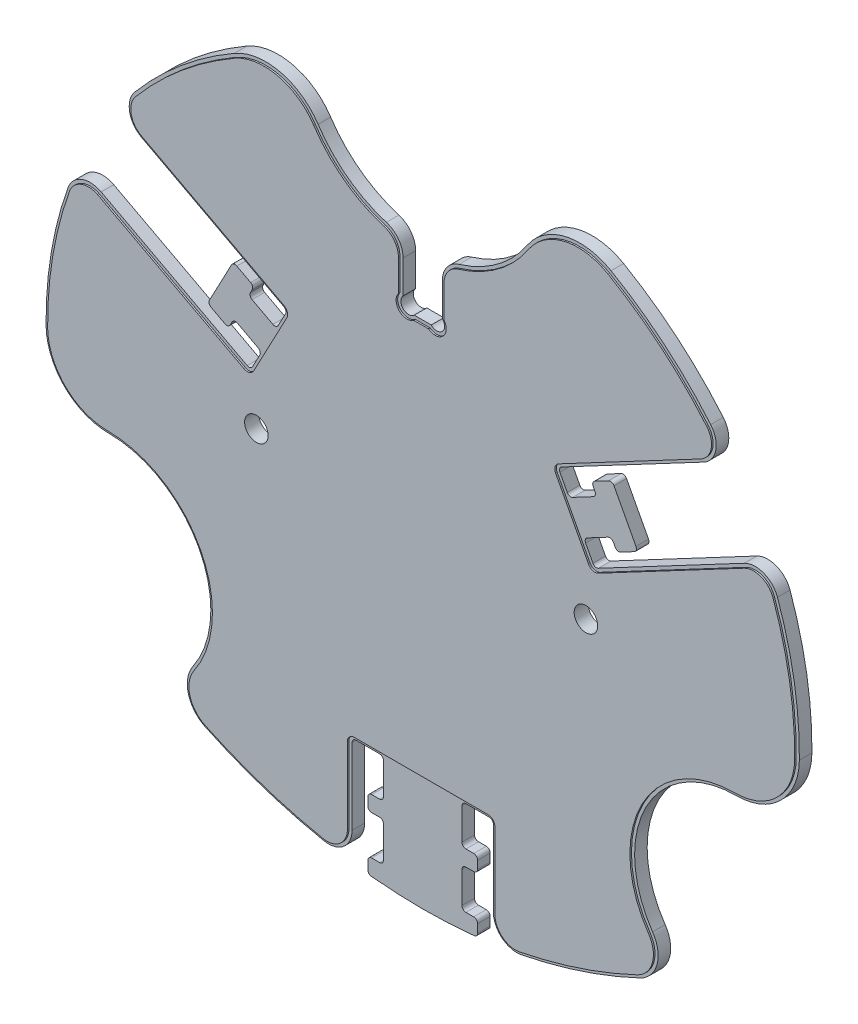
SolidWorks part; units mm, degrees
ref_plane "Plan de face" through (0, 0, 0) normal (0, 0, 1) x (1, 0, 0)
ref_plane "Plan de dessus" through (0, 0, 0) normal (0, 1, 0) x (1, 0, 0)
ref_plane "Plan de droite" through (0, 0, 0) normal (1, 0, 0) x (0, 0, -1)
sketch "Esquisse1" plane through (0, 0, 0) normal (0, 0, 1) x (1, 0, 0)
  line L0 (-25, 70) -> (-25, 0) construction
  line L1 (-25, 0) -> (25, 0) construction
  line L2 (25, 0) -> (25, 70) construction
  line L3 (25, 70) -> (-25, 70) construction
  line L4 (0, 70) -> (0, 0) construction
  line L5 (-25, 42.594) -> (25, 42.594) construction
  line L6 (15.5429, -26.8302) -> (15.4017, -26.5477) construction
  line L7 (40, 19.5) -> (0, 42.594) construction
  line L8 (0, 42.594) -> (-40, 19.5) construction
  line L9 (41.6817, 64.6801) -> (0, 42.594) construction
  line L10 (0, 0) -> (24.9579, 0) construction
  line L11 (43.9325, 60.2142) -> (21.9323, 48.5568)
  line L12 (21.9323, 48.5568) -> (20.5277, 51.2077)
  line L13 (20.5277, 51.2077) -> (24.0621, 53.0805)
  line L14 (24.0621, 53.0805) -> (24.7645, 51.7551)
  line L15 (24.7645, 51.7551) -> (27.4153, 53.1597)
  line L16 (27.4153, 53.1597) -> (24.1379, 59.345)
  line L17 (24.1379, 59.345) -> (21.487, 57.9404)
  line L18 (21.487, 57.9404) -> (22.1893, 56.615)
  line L19 (22.1893, 56.615) -> (18.6548, 54.7421)
  line L20 (18.6548, 54.7421) -> (17.2502, 57.393)
  line L21 (17.2502, 57.393) -> (38.9688, 68.9011)
  line L22 (-43.9325, 60.2142) -> (-21.9323, 48.5568)
  line L23 (-21.9323, 48.5568) -> (-20.5277, 51.2077)
  line L24 (-20.5277, 51.2077) -> (-24.0621, 53.0805)
  line L25 (-24.0621, 53.0805) -> (-24.7645, 51.7551)
  line L26 (-24.7645, 51.7551) -> (-27.4153, 53.1597)
  line L27 (-27.4153, 53.1597) -> (-24.1379, 59.345)
  line L28 (-24.1379, 59.345) -> (-21.487, 57.9404)
  line L29 (-21.487, 57.9404) -> (-22.1893, 56.615)
  line L30 (-22.1893, 56.615) -> (-18.6548, 54.7421)
  line L31 (-18.6548, 54.7421) -> (-17.2502, 57.393)
  line L32 (-17.2502, 57.393) -> (-38.9688, 68.9011)
  line L33 (-9, 0.6296) -> (-9, 14.3801)
  line L34 (-9, 14.3801) -> (-5, 14.3801)
  line L35 (-5, 14.3801) -> (-5, 2.3801) construction
  line L36 (-5, 2.3801) -> (-7, 2.3801)
  line L37 (-7, 2.3801) -> (-7, 0.3801)
  line L38 (-7, 0.3801) -> (7, 0.3801) construction
  line L39 (7, 0.3801) -> (7, 2.3801)
  line L40 (7, 2.3801) -> (5, 2.3801)
  line L41 (5, 2.3801) -> (5, 14.3801) construction
  line L42 (5, 14.3801) -> (9, 14.3801)
  line L43 (9, 14.3801) -> (9, 0.6296)
  line L44 (-5, 14.3801) -> (-5, 9.3801)
  line L45 (-5, 9.3801) -> (-7, 9.3801)
  line L46 (-7, 9.3801) -> (-7, 7.3801)
  line L47 (-7, 7.3801) -> (-5, 7.3801)
  line L48 (-5, 7.3801) -> (-5, 2.3801)
  line L49 (5, 7.3801) -> (5, 2.3801)
  line L50 (7, 7.3801) -> (5, 7.3801)
  line L51 (7, 9.3801) -> (7, 7.3801)
  line L52 (5, 9.3801) -> (7, 9.3801)
  line L53 (5, 14.3801) -> (5, 9.3801)
  line L54 (-2.5, 72.9786) -> (-2.5, 65) construction
  line L55 (-2.5, 65) -> (2.5, 65) construction
  line L56 (2.5, 65) -> (2.5, 72.9786) construction
  line L57 (2.5, 72.9786) -> (2.5, 66.4142)
  line L58 (1.0858, 65) -> (-1.0858, 65)
  line L59 (-2.5, 72.9786) -> (-2.5, 66.4142)
  line L60 (2.5, 65) -> (1.7929, 65.7071) construction
  circle A0 centre (40, 19.5) radius 10 construction
  circle A1 centre (-40, 19.5) radius 10 construction
  circle A2 centre (0, 88.782) radius 10 construction
  arc A3 (40, 32.5) -> (29.2941, 12.1254) centre (40, 19.5) ccw
  arc A4 (40, 32.5) -> (47.9997, 40.4255) centre (40, 40.5) ccw
  arc A5 (23.9998, 82.4438) -> (47.9997, 40.4255) centre (0, 40.8725) cw construction
  arc A6 (23.9998, 82.4438) -> (13.3333, 79.9377) centre (20, 75.5155) ccw
  arc A7 (13.3333, 79.9377) -> (-13.3333, 79.9377) centre (0, 88.782) cw construction
  arc A8 (29.2941, 12.1254) -> (27.7149, 6.2426) centre (26, 9.8563) cw
  arc A9 (27.7149, 6.2426) -> (-27.7149, 6.2426) centre (0, 64.6433) cw construction
  arc A10 (-29.2941, 12.1254) -> (-27.7149, 6.2426) centre (-26, 9.8563) ccw
  arc A11 (-40, 32.5) -> (-29.2941, 12.1254) centre (-40, 19.5) cw
  arc A12 (-40, 32.5) -> (-47.9997, 40.4255) centre (-40, 40.5) cw
  arc A13 (-23.9998, 82.4438) -> (-47.9997, 40.4255) centre (0, 40.8725) ccw construction
  arc A14 (-23.9998, 82.4438) -> (-13.3333, 79.9377) centre (-20, 75.5155) cw
  circle A15 centre (-21, 42.594) radius 1.5
  circle A16 centre (21, 42.594) radius 1.5
  arc A17 (23.9998, 82.4438) -> (38.9688, 68.9011) centre (0, 40.8725) cw
  arc A18 (43.9325, 60.2142) -> (47.9997, 40.4255) centre (0, 40.8725) cw
  arc A19 (-43.9325, 60.2142) -> (-47.9997, 40.4255) centre (0, 40.8725) ccw
  arc A20 (-23.9998, 82.4438) -> (-38.9688, 68.9011) centre (0, 40.8725) ccw
  arc A21 (9, 0.6296) -> (27.7149, 6.2426) centre (0, 64.6433) ccw
  arc A22 (-9, 0.6296) -> (-27.7149, 6.2426) centre (0, 64.6433) cw
  arc A23 (-7, 0.3801) -> (7, 0.3801) centre (0, 64.6433) ccw
  arc A24 (-2.5, 72.9786) -> (-13.3333, 79.9377) centre (0, 88.782) cw
  arc A25 (2.5, 72.9786) -> (13.3333, 79.9377) centre (0, 88.782) ccw
  arc A26 (2.5, 66.4142) -> (1.0858, 65) centre (1.7929, 65.7071) cw
  arc A27 (-2.5, 66.4142) -> (-1.0858, 65) centre (-1.7929, 65.7071) ccw
  point P10 (-21, 42.594)
  point P12 (21, 42.594)
  point P95 (9, 14.3801)
  point P96 (-9, 14.3801)
  point P111 (-1.1363, 65)
  dimension "D3" = 20
  dimension "D10" = 8
  dimension "D12" = 8
  dimension "D14" = 4
  dimension "D19" = 3
  dimension "D44" = 1
  dimension "D1" = 70
  dimension "D2" = 50
  dimension "D4" = 19.5
  dimension "D5" = 80
  dimension "D6" = 80
  dimension "D7" = 42
  dimension "D9" = 6
  dimension "D11" = 3
  dimension "D15" = 40
  dimension "D16" = 20
  dimension "D17" = 1
  dimension "D18" = 26
  dimension "D20" = 120
  dimension "D8" = 4
  dimension "D21" = 4
  dimension "D22" = 7
  dimension "D23" = 5
  dimension "D24" = 5
  dimension "D25" = 4
  dimension "D26" = 7
  dimension "D27" = 4
  dimension "D28" = 3
  dimension "D29" = 25
  dimension "D30" = 10
  dimension "D31" = 14
  dimension "D32" = 10
  dimension "D33" = 10
  dimension "D34" = 2
  dimension "D35" = 4
  dimension "D36" = 18
  dimension "D37" = 2
  dimension "D38" = 5
  dimension "D39" = 5
  dimension "D40" = 2
  dimension "D41" = 65
  dimension "D13" = 5
  dimension "D42" = 5
  dimension "D43" = 45
extrude "Boss.-Extru.1" add sketch "Esquisse1" along normal blind 1.6
fillet "Congé5" radius 0.5 38 edges at (-24.0621, 53.0805, 0.8) (-21.9323, 48.5568, 0.8) (-27.4153, 53.1597, 0.8) (-24.7645, 51.7551, 0.8) (-20.5277, 51.2077, 0.8) (-17.2502, 57.393, 0.8) (-18.6548, 54.7421, 0.8) (-22.1893, 56.615, 0.8) (-24.1379, 59.345, 0.8) (-21.487, 57.9404, 0.8) (17.2502, 57.393, 0.8) (18.6548, 54.7421, 0.8) (24.1379, 59.345, 0.8) (21.487, 57.9404, 0.8) (22.1893, 56.615, 0.8) (21.9323, 48.5568, 0.8) (20.5277, 51.2077, 0.8) (24.0621, 53.0805, 0.8) (24.7645, 51.7551, 0.8) (27.4153, 53.1597, 0.8) (9, 14.3801, 0.8) (-5, 14.3801, 0.8) (-7, 0.3801, 0.8) (7, 0.3801, 0.8) (5, 2.3801, 0.8) (7, 2.3801, 0.8) (-7, 2.3801, 0.8) (-5, 2.3801, 0.8) (-5, 9.3801, 0.8) (-7, 9.3801, 0.8) (-5, 7.3801, 0.8) (-7, 7.3801, 0.8) (-9, 14.3801, 0.8) (5, 7.3801, 0.8) (7, 7.3801, 0.8) (7, 9.3801, 0.8) (5, 9.3801, 0.8) (5, 14.3801, 0.8)
fillet "Congé6" radius 3 8 edges at (-38.9688, 68.9011, 0.8) (-43.9325, 60.2142, 0.8) (43.9325, 60.2142, 0.8) (38.9688, 68.9011, 0.8) (-9, 0.6296, 0.8) (9, 0.6296, 0.8) (2.5, 72.9786, 0.8) (-2.5, 72.9786, 0.8)
sketch "Esquisse2" plane through (0, 0, 1.6) normal (0, 0, 1) x (1, 0, 0)
  line L0 (17.1309, 56.7639) -> (21.3447, 48.8113)
  line L1 (8.5, 14.7801) -> (-8.5, 14.7801)
  line L2 (-17.1309, 56.7639) -> (-21.3447, 48.8113)
  line L22 (41.1662, 58.2957) -> (22.5614, 48.4375)
  line L23 (41.1662, 58.2957) -> (22.5614, 48.4375)
  line L24 (21.3447, 48.8113) -> (20.4083, 50.5786)
  line L25 (21.3447, 48.8113) -> (20.4083, 50.5786) construction
  line L26 (20.7822, 51.7952) -> (23.4331, 53.1998)
  line L27 (20.7822, 51.7952) -> (23.4331, 53.1998) construction
  line L28 (24.6497, 52.826) -> (24.8838, 52.3842)
  line L29 (24.6497, 52.826) -> (24.8838, 52.3842) construction
  line L30 (25.019, 52.3426) -> (26.7862, 53.279)
  line L31 (25.019, 52.3426) -> (26.7862, 53.279) construction
  line L32 (26.8278, 53.4142) -> (24.0185, 58.7159)
  line L33 (26.8278, 53.4142) -> (24.0185, 58.7159) construction
  line L34 (23.8833, 58.7575) -> (22.1161, 57.8211)
  line L35 (23.8833, 58.7575) -> (22.1161, 57.8211) construction
  line L36 (22.0746, 57.6859) -> (22.3087, 57.2441)
  line L37 (22.0746, 57.6859) -> (22.3087, 57.2441) construction
  line L38 (21.9348, 56.0274) -> (19.2839, 54.6228)
  line L39 (21.9348, 56.0274) -> (19.2839, 54.6228) construction
  line L40 (18.0673, 54.9967) -> (17.1309, 56.7639)
  line L41 (18.0673, 54.9967) -> (17.1309, 56.7639) construction
  line L42 (17.5047, 57.9806) -> (35.6237, 67.5813)
  line L43 (17.5047, 57.9806) -> (35.6237, 67.5813)
  line L44 (-35.6237, 67.5813) -> (-17.5047, 57.9806)
  line L45 (-35.6237, 67.5813) -> (-17.5047, 57.9806)
  line L46 (-17.1309, 56.7639) -> (-18.0673, 54.9967)
  line L47 (-17.1309, 56.7639) -> (-18.0673, 54.9967) construction
  line L48 (-19.2839, 54.6228) -> (-21.9348, 56.0274)
  line L49 (-19.2839, 54.6228) -> (-21.9348, 56.0274) construction
  line L50 (-22.3087, 57.2441) -> (-22.0746, 57.6859)
  line L51 (-22.3087, 57.2441) -> (-22.0746, 57.6859) construction
  line L52 (-22.1161, 57.8211) -> (-23.8833, 58.7575)
  line L53 (-22.1161, 57.8211) -> (-23.8833, 58.7575) construction
  line L54 (-24.0185, 58.7159) -> (-26.8278, 53.4142)
  line L55 (-24.0185, 58.7159) -> (-26.8278, 53.4142) construction
  line L56 (-26.7862, 53.279) -> (-25.019, 52.3426)
  line L57 (-26.7862, 53.279) -> (-25.019, 52.3426) construction
  line L58 (-24.8838, 52.3842) -> (-24.6497, 52.826)
  line L59 (-24.8838, 52.3842) -> (-24.6497, 52.826) construction
  line L60 (-23.4331, 53.1998) -> (-20.7822, 51.7952)
  line L61 (-23.4331, 53.1998) -> (-20.7822, 51.7952) construction
  line L62 (-20.4083, 50.5786) -> (-21.3447, 48.8113)
  line L63 (-20.4083, 50.5786) -> (-21.3447, 48.8113) construction
  line L64 (-22.5614, 48.4375) -> (-41.1662, 58.2957)
  line L65 (-22.5614, 48.4375) -> (-41.1662, 58.2957)
  line L87 (-9.4, 4.1793) -> (-9.4, 13.8801)
  line L88 (-9.4, 4.1793) -> (-9.4, 13.8801)
  line L89 (-8.5, 14.7801) -> (-5.5, 14.7801)
  line L90 (-8.5, 14.7801) -> (-5.5, 14.7801) construction
  line L91 (-4.6, 13.8801) -> (-4.6, 9.8801)
  line L92 (-4.6, 13.8801) -> (-4.6, 9.8801) construction
  line L93 (-5.5, 8.9801) -> (-6.5, 8.9801)
  line L94 (-5.5, 8.9801) -> (-6.5, 8.9801) construction
  line L95 (-6.6, 8.8801) -> (-6.6, 7.8801)
  line L96 (-6.6, 8.8801) -> (-6.6, 7.8801) construction
  line L97 (-6.5, 7.7801) -> (-5.5, 7.7801)
  line L98 (-6.5, 7.7801) -> (-5.5, 7.7801) construction
  line L99 (-4.6, 6.8801) -> (-4.6, 2.8801)
  line L100 (-4.6, 6.8801) -> (-4.6, 2.8801) construction
  line L101 (-5.5, 1.9801) -> (-6.5, 1.9801)
  line L102 (-5.5, 1.9801) -> (-6.5, 1.9801) construction
  line L103 (-6.6, 1.8801) -> (-6.6, 0.8302)
  line L104 (-6.6, 1.8801) -> (-6.6, 0.8302) construction
  line L105 (6.6, 0.8302) -> (6.6, 1.8801)
  line L106 (6.6, 0.8302) -> (6.6, 1.8801) construction
  line L107 (6.5, 1.9801) -> (5.5, 1.9801)
  line L108 (6.5, 1.9801) -> (5.5, 1.9801) construction
  line L109 (4.6, 2.8801) -> (4.6, 6.8801)
  line L110 (4.6, 2.8801) -> (4.6, 6.8801) construction
  line L111 (5.5, 7.7801) -> (6.5, 7.7801)
  line L112 (5.5, 7.7801) -> (6.5, 7.7801) construction
  line L113 (6.6, 7.8801) -> (6.6, 8.8801)
  line L114 (6.6, 7.8801) -> (6.6, 8.8801) construction
  line L115 (6.5, 8.9801) -> (5.5, 8.9801)
  line L116 (6.5, 8.9801) -> (5.5, 8.9801) construction
  line L117 (4.6, 9.8801) -> (4.6, 13.8801)
  line L118 (4.6, 9.8801) -> (4.6, 13.8801) construction
  line L119 (5.5, 14.7801) -> (8.5, 14.7801)
  line L120 (5.5, 14.7801) -> (8.5, 14.7801) construction
  line L121 (9.4, 13.8801) -> (9.4, 4.1793)
  line L122 (9.4, 13.8801) -> (9.4, 4.1793)
  line L123 (2.9, 70.5955) -> (2.9, 66.564)
  line L124 (2.9, 70.5955) -> (2.9, 66.564)
  line L125 (0.936, 64.6) -> (-0.936, 64.6)
  line L126 (0.936, 64.6) -> (-0.936, 64.6)
  line L127 (-2.9, 66.564) -> (-2.9, 70.5955)
  line L128 (-2.9, 66.564) -> (-2.9, 70.5955)
  circle A19 centre (-21, 42.594) radius 1.5
  circle A20 centre (21, 42.594) radius 1.5
  circle A21 centre (21, 42.594) radius 1.5 construction
  circle A22 centre (-21, 42.594) radius 1.5 construction
  arc A25 (-44.8323, 56.8722) -> (-47.5997, 40.4292) centre (0, 40.8725) ccw
  arc A26 (23.7998, 82.0974) -> (13.6667, 79.7166) centre (20, 75.5155) ccw
  arc A27 (-36.3942, 71.5546) -> (-35.6237, 67.5813) centre (-34.4063, 69.8787) ccw
  arc A28 (-13.6667, 79.7166) -> (-23.7998, 82.0974) centre (-20, 75.5155) ccw
  arc A29 (-44.8323, 56.8722) -> (-47.5997, 40.4292) centre (0, 40.8725) ccw
  arc A30 (-47.5997, 40.4292) -> (-40, 32.9) centre (-40, 40.5) ccw
  arc A31 (-28.9647, 11.8985) -> (-40, 32.9) centre (-40, 19.5) ccw
  arc A32 (-28.9647, 11.8985) -> (-27.5435, 6.604) centre (-26, 9.8563) ccw
  arc A33 (-36.3942, 71.5546) -> (-35.6237, 67.5813) centre (-34.4063, 69.8787) ccw
  arc A34 (27.5435, 6.604) -> (28.9647, 11.8985) centre (26, 9.8563) ccw
  arc A35 (40, 32.9) -> (28.9647, 11.8985) centre (40, 19.5) ccw
  arc A36 (40, 32.9) -> (47.5997, 40.4292) centre (40, 40.5) ccw
  arc A38 (23.7998, 82.0974) -> (13.6667, 79.7166) centre (20, 75.5155) ccw
  arc A40 (-13.6667, 79.7166) -> (-23.7998, 82.0974) centre (-20, 75.5155) ccw
  arc A42 (-47.5997, 40.4292) -> (-40, 32.9) centre (-40, 40.5) ccw
  arc A43 (-28.9647, 11.8985) -> (-40, 32.9) centre (-40, 19.5) ccw
  arc A44 (-28.9647, 11.8985) -> (-27.5435, 6.604) centre (-26, 9.8563) ccw
  arc A46 (27.5435, 6.604) -> (28.9647, 11.8985) centre (26, 9.8563) ccw
  arc A47 (40, 32.9) -> (28.9647, 11.8985) centre (40, 19.5) ccw
  arc A48 (40, 32.9) -> (47.5997, 40.4292) centre (40, 40.5) ccw
  arc A61 (47.5997, 40.4292) -> (44.8323, 56.8722) centre (0, 40.8725) ccw
  arc A62 (47.5997, 40.4292) -> (44.8323, 56.8722) centre (0, 40.8725) ccw
  arc A63 (36.3942, 71.5546) -> (23.7998, 82.0974) centre (0, 40.8725) ccw
  arc A64 (36.3942, 71.5546) -> (23.7998, 82.0974) centre (0, 40.8725) ccw
  arc A65 (-23.7998, 82.0974) -> (-36.3942, 71.5546) centre (0, 40.8725) ccw
  arc A66 (-23.7998, 82.0974) -> (-36.3942, 71.5546) centre (0, 40.8725) ccw
  arc A96 (-17.1309, 56.7639) -> (-17.5047, 57.9806) centre (-17.9261, 57.1853) ccw
  arc A97 (-17.1309, 56.7639) -> (-17.5047, 57.9806) centre (-17.9261, 57.1853) ccw
  arc A98 (-19.2839, 54.6228) -> (-18.0673, 54.9967) centre (-18.8625, 55.4181) ccw
  arc A99 (-19.2839, 54.6228) -> (-18.0673, 54.9967) centre (-18.8625, 55.4181) ccw construction
  arc A100 (-22.3087, 57.2441) -> (-21.9348, 56.0274) centre (-21.5134, 56.8227) ccw
  arc A101 (-22.3087, 57.2441) -> (-21.9348, 56.0274) centre (-21.5134, 56.8227) ccw construction
  arc A102 (-22.0746, 57.6859) -> (-22.1161, 57.8211) centre (-22.1629, 57.7327) ccw
  arc A103 (-22.0746, 57.6859) -> (-22.1161, 57.8211) centre (-22.1629, 57.7327) ccw construction
  arc A104 (-23.8833, 58.7575) -> (-24.0185, 58.7159) centre (-23.9302, 58.6691) ccw
  arc A105 (-23.8833, 58.7575) -> (-24.0185, 58.7159) centre (-23.9302, 58.6691) ccw construction
  arc A106 (-26.8278, 53.4142) -> (-26.7862, 53.279) centre (-26.7394, 53.3674) ccw
  arc A107 (-26.8278, 53.4142) -> (-26.7862, 53.279) centre (-26.7394, 53.3674) ccw construction
  arc A108 (-25.019, 52.3426) -> (-24.8838, 52.3842) centre (-24.9722, 52.431) ccw
  arc A109 (-25.019, 52.3426) -> (-24.8838, 52.3842) centre (-24.9722, 52.431) ccw construction
  arc A110 (-23.4331, 53.1998) -> (-24.6497, 52.826) centre (-23.8544, 52.4046) ccw
  arc A111 (-23.4331, 53.1998) -> (-24.6497, 52.826) centre (-23.8544, 52.4046) ccw construction
  arc A112 (-20.4083, 50.5786) -> (-20.7822, 51.7952) centre (-21.2036, 51) ccw
  arc A113 (-20.4083, 50.5786) -> (-20.7822, 51.7952) centre (-21.2036, 51) ccw construction
  arc A114 (-22.5614, 48.4375) -> (-21.3447, 48.8113) centre (-22.14, 49.2327) ccw
  arc A115 (-22.5614, 48.4375) -> (-21.3447, 48.8113) centre (-22.14, 49.2327) ccw
  arc A116 (-41.1662, 58.2957) -> (-44.8323, 56.8722) centre (-42.3836, 55.9983) ccw
  arc A117 (-41.1662, 58.2957) -> (-44.8323, 56.8722) centre (-42.3836, 55.9983) ccw
  arc A118 (-27.5435, 6.604) -> (-12.5061, 1.629) centre (0, 64.6433) ccw
  arc A119 (-27.5435, 6.604) -> (-12.5061, 1.629) centre (0, 64.6433) ccw
  arc A120 (-6.5101, 0.7307) -> (6.5101, 0.7307) centre (0, 64.6433) ccw
  arc A121 (-6.5101, 0.7307) -> (6.5101, 0.7307) centre (0, 64.6433) ccw construction
  arc A122 (12.5061, 1.629) -> (27.5435, 6.604) centre (0, 64.6433) ccw
  arc A123 (12.5061, 1.629) -> (27.5435, 6.604) centre (0, 64.6433) ccw
  arc A124 (44.8323, 56.8722) -> (41.1662, 58.2957) centre (42.3836, 55.9983) ccw
  arc A125 (44.8323, 56.8722) -> (41.1662, 58.2957) centre (42.3836, 55.9983) ccw
  arc A126 (21.3447, 48.8113) -> (22.5614, 48.4375) centre (22.14, 49.2327) ccw
  arc A127 (21.3447, 48.8113) -> (22.5614, 48.4375) centre (22.14, 49.2327) ccw
  arc A128 (20.7822, 51.7952) -> (20.4083, 50.5786) centre (21.2036, 51) ccw
  arc A129 (20.7822, 51.7952) -> (20.4083, 50.5786) centre (21.2036, 51) ccw construction
  arc A130 (24.6497, 52.826) -> (23.4331, 53.1998) centre (23.8544, 52.4046) ccw
  arc A131 (24.6497, 52.826) -> (23.4331, 53.1998) centre (23.8544, 52.4046) ccw construction
  arc A132 (24.8838, 52.3842) -> (25.019, 52.3426) centre (24.9722, 52.431) ccw
  arc A133 (24.8838, 52.3842) -> (25.019, 52.3426) centre (24.9722, 52.431) ccw construction
  arc A134 (26.7862, 53.279) -> (26.8278, 53.4142) centre (26.7394, 53.3674) ccw
  arc A135 (26.7862, 53.279) -> (26.8278, 53.4142) centre (26.7394, 53.3674) ccw construction
  arc A136 (24.0185, 58.7159) -> (23.8833, 58.7575) centre (23.9302, 58.6691) ccw
  arc A137 (24.0185, 58.7159) -> (23.8833, 58.7575) centre (23.9302, 58.6691) ccw construction
  arc A138 (22.1161, 57.8211) -> (22.0746, 57.6859) centre (22.1629, 57.7327) ccw
  arc A139 (22.1161, 57.8211) -> (22.0746, 57.6859) centre (22.1629, 57.7327) ccw construction
  arc A140 (21.9348, 56.0274) -> (22.3087, 57.2441) centre (21.5134, 56.8227) ccw
  arc A141 (21.9348, 56.0274) -> (22.3087, 57.2441) centre (21.5134, 56.8227) ccw construction
  arc A142 (18.0673, 54.9967) -> (19.2839, 54.6228) centre (18.8625, 55.4181) ccw
  arc A143 (18.0673, 54.9967) -> (19.2839, 54.6228) centre (18.8625, 55.4181) ccw construction
  arc A144 (17.5047, 57.9806) -> (17.1309, 56.7639) centre (17.9261, 57.1853) ccw
  arc A145 (17.5047, 57.9806) -> (17.1309, 56.7639) centre (17.9261, 57.1853) ccw
  arc A146 (35.6237, 67.5813) -> (36.3942, 71.5546) centre (34.4063, 69.8787) ccw
  arc A147 (35.6237, 67.5813) -> (36.3942, 71.5546) centre (34.4063, 69.8787) ccw
  arc A148 (4.7474, 73.0842) -> (13.6667, 79.7166) centre (0, 88.782) ccw
  arc A149 (4.7474, 73.0842) -> (13.6667, 79.7166) centre (0, 88.782) ccw
  arc A150 (0.936, 64.6) -> (2.9, 66.564) centre (1.7929, 65.7071) ccw
  arc A151 (0.936, 64.6) -> (2.9, 66.564) centre (1.7929, 65.7071) ccw
  arc A152 (-2.9, 66.564) -> (-0.936, 64.6) centre (-1.7929, 65.7071) ccw
  arc A153 (-2.9, 66.564) -> (-0.936, 64.6) centre (-1.7929, 65.7071) ccw
  arc A154 (-13.6667, 79.7166) -> (-4.7474, 73.0842) centre (0, 88.782) ccw
  arc A155 (-13.6667, 79.7166) -> (-4.7474, 73.0842) centre (0, 88.782) ccw
  arc A174 (-8.5, 14.7801) -> (-9.4, 13.8801) centre (-8.5, 13.8801) ccw
  arc A175 (-8.5, 14.7801) -> (-9.4, 13.8801) centre (-8.5, 13.8801) ccw
  arc A176 (-4.6, 13.8801) -> (-5.5, 14.7801) centre (-5.5, 13.8801) ccw
  arc A177 (-4.6, 13.8801) -> (-5.5, 14.7801) centre (-5.5, 13.8801) ccw construction
  arc A178 (-5.5, 8.9801) -> (-4.6, 9.8801) centre (-5.5, 9.8801) ccw
  arc A179 (-5.5, 8.9801) -> (-4.6, 9.8801) centre (-5.5, 9.8801) ccw construction
  arc A180 (-6.5, 8.9801) -> (-6.6, 8.8801) centre (-6.5, 8.8801) ccw
  arc A181 (-6.5, 8.9801) -> (-6.6, 8.8801) centre (-6.5, 8.8801) ccw construction
  arc A182 (-6.6, 7.8801) -> (-6.5, 7.7801) centre (-6.5, 7.8801) ccw
  arc A183 (-6.6, 7.8801) -> (-6.5, 7.7801) centre (-6.5, 7.8801) ccw construction
  arc A184 (-4.6, 6.8801) -> (-5.5, 7.7801) centre (-5.5, 6.8801) ccw
  arc A185 (-4.6, 6.8801) -> (-5.5, 7.7801) centre (-5.5, 6.8801) ccw construction
  arc A186 (-5.5, 1.9801) -> (-4.6, 2.8801) centre (-5.5, 2.8801) ccw
  arc A187 (-5.5, 1.9801) -> (-4.6, 2.8801) centre (-5.5, 2.8801) ccw construction
  arc A188 (-6.5, 1.9801) -> (-6.6, 1.8801) centre (-6.5, 1.8801) ccw
  arc A189 (-6.5, 1.9801) -> (-6.6, 1.8801) centre (-6.5, 1.8801) ccw construction
  arc A190 (-6.6, 0.8302) -> (-6.5101, 0.7307) centre (-6.5, 0.8302) ccw
  arc A191 (-6.6, 0.8302) -> (-6.5101, 0.7307) centre (-6.5, 0.8302) ccw construction
  arc A192 (6.5101, 0.7307) -> (6.6, 0.8302) centre (6.5, 0.8302) ccw
  arc A193 (6.5101, 0.7307) -> (6.6, 0.8302) centre (6.5, 0.8302) ccw construction
  arc A194 (6.6, 1.8801) -> (6.5, 1.9801) centre (6.5, 1.8801) ccw
  arc A195 (6.6, 1.8801) -> (6.5, 1.9801) centre (6.5, 1.8801) ccw construction
  arc A196 (4.6, 2.8801) -> (5.5, 1.9801) centre (5.5, 2.8801) ccw
  arc A197 (4.6, 2.8801) -> (5.5, 1.9801) centre (5.5, 2.8801) ccw construction
  arc A198 (5.5, 7.7801) -> (4.6, 6.8801) centre (5.5, 6.8801) ccw
  arc A199 (5.5, 7.7801) -> (4.6, 6.8801) centre (5.5, 6.8801) ccw construction
  arc A200 (6.5, 7.7801) -> (6.6, 7.8801) centre (6.5, 7.8801) ccw
  arc A201 (6.5, 7.7801) -> (6.6, 7.8801) centre (6.5, 7.8801) ccw construction
  arc A202 (6.6, 8.8801) -> (6.5, 8.9801) centre (6.5, 8.8801) ccw
  arc A203 (6.6, 8.8801) -> (6.5, 8.9801) centre (6.5, 8.8801) ccw construction
  arc A204 (4.6, 9.8801) -> (5.5, 8.9801) centre (5.5, 9.8801) ccw
  arc A205 (4.6, 9.8801) -> (5.5, 8.9801) centre (5.5, 9.8801) ccw construction
  arc A206 (5.5, 14.7801) -> (4.6, 13.8801) centre (5.5, 13.8801) ccw
  arc A207 (5.5, 14.7801) -> (4.6, 13.8801) centre (5.5, 13.8801) ccw construction
  arc A208 (9.4, 13.8801) -> (8.5, 14.7801) centre (8.5, 13.8801) ccw
  arc A209 (9.4, 13.8801) -> (8.5, 14.7801) centre (8.5, 13.8801) ccw
  arc A212 (-12.5061, 1.629) -> (-9.4, 4.1793) centre (-12, 4.1793) ccw
  arc A213 (-12.5061, 1.629) -> (-9.4, 4.1793) centre (-12, 4.1793) ccw
  arc A214 (9.4, 4.1793) -> (12.5061, 1.629) centre (12, 4.1793) ccw
  arc A215 (9.4, 4.1793) -> (12.5061, 1.629) centre (12, 4.1793) ccw
  arc A218 (4.7474, 73.0842) -> (2.9, 70.5955) centre (5.5, 70.5955) ccw
  arc A219 (4.7474, 73.0842) -> (2.9, 70.5955) centre (5.5, 70.5955) ccw
  arc A220 (-2.9, 70.5955) -> (-4.7474, 73.0842) centre (-5.5, 70.5955) ccw
  arc A221 (-2.9, 70.5955) -> (-4.7474, 73.0842) centre (-5.5, 70.5955) ccw
  dimension "D1" = 0.4
extrude "Boss.-Extru.2" add sketch "Esquisse2" along normal blind 0.2
equation "\"D12@Esquisse1\"=\"D10@Esquisse1\""
equation "\"D24@Esquisse1\"=\"D23@Esquisse1\""
equation "\"D26@Esquisse1\"=\"D23@Esquisse1\"*2-3"
equation "\"D25@Esquisse1\"=\"D23@Esquisse1\"*2-6"
